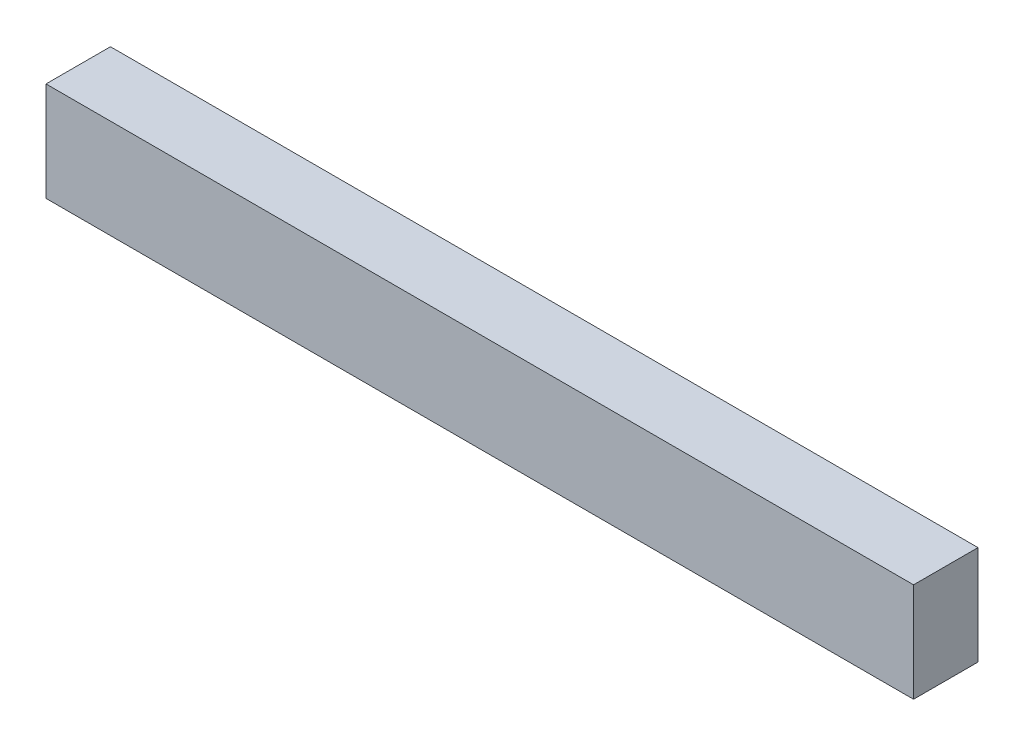
SolidWorks part; units mm, degrees
ref_plane "Płaszczyzna przednia" through (0, 0, 0) normal (0, 0, 1) x (1, 0, 0)
ref_plane "Płaszczyzna górna" through (0, 0, 0) normal (0, 1, 0) x (1, 0, 0)
ref_plane "Płaszczyzna prawa" through (0, 0, 0) normal (1, 0, 0) x (0, 0, -1)
sketch "Szkic1" plane through (0, 0, 0) normal (0, 0, 1) x (1, 0, 0)
  line L1 (-17.5, -2) -> (17.5, -2)
  line L2 (-17.5, -2) -> (-17.5, 2)
  line L3 (-17.5, 2) -> (17.5, 2)
  line L4 (17.5, -2) -> (17.5, 2)
  line L5 (-17.5, -2) -> (17.5, 2) construction
  line L6 (-17.5, 2) -> (17.5, -2) construction
  point P0 (0, 0)
  dimension "D1" = 35
  dimension "D2" = 4
extrude "Dodanie-wyciągnięcie1" add sketch "Szkic1" along normal blind 2.6
